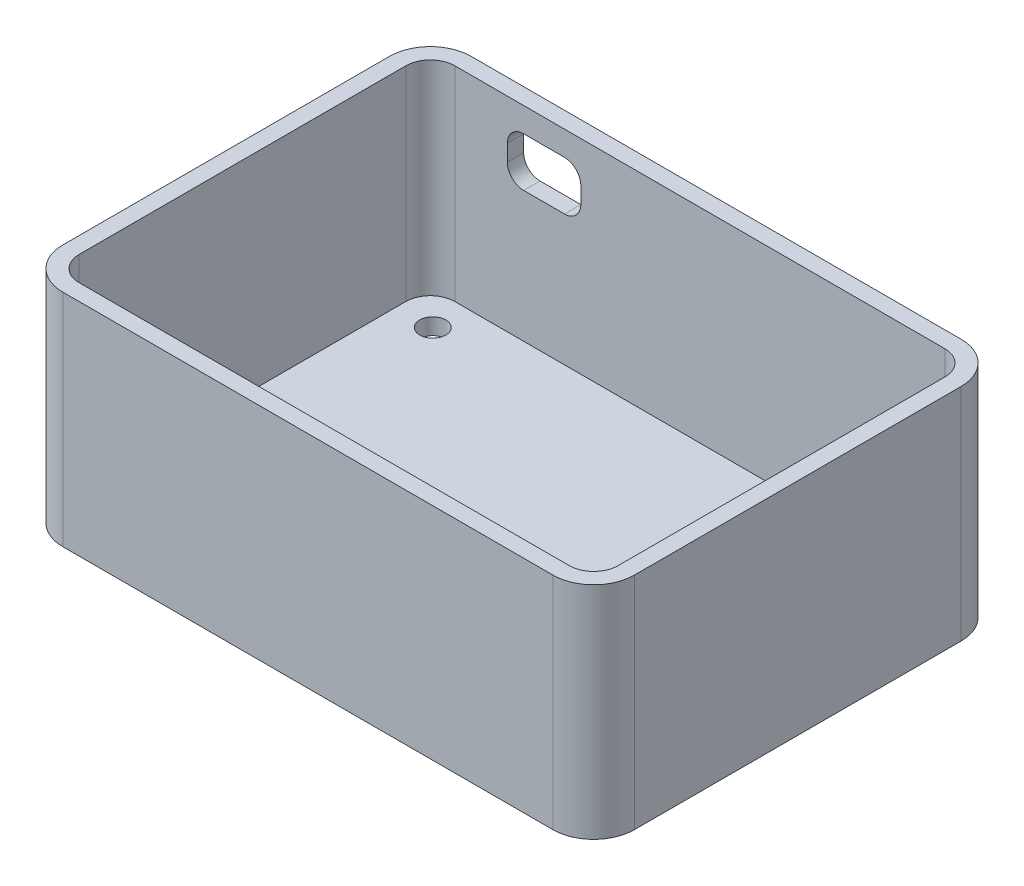
SolidWorks part; units mm, degrees
ref_plane "Front Plane" through (0, 0, 0) normal (0, 0, 1) x (1, 0, 0)
ref_plane "Top Plane" through (0, 0, 0) normal (0, 1, 0) x (1, 0, 0)
ref_plane "Right Plane" through (0, 0, 0) normal (1, 0, 0) x (0, 0, -1)
sketch "Sketch1" plane through (0, 0, 0) normal (0, 1, 0) x (1, 0, 0)
  line L0 (35, 0) -> (35, -50) construction
  line L1 (5, 0) -> (65, 0)
  line L2 (0, -5) -> (0, -45)
  line L3 (5, -50) -> (65, -50)
  line L4 (70, -5) -> (70, -45)
  line L5 (0, -25) -> (70, -25) construction
  circle A0 centre (6.4, -6.1) radius 1.6
  circle A1 centre (63.6, -6.1) radius 1.6
  circle A2 centre (6.4, -43.9) radius 1.6
  circle A3 centre (63.6, -43.9) radius 1.6
  arc A4 (65, -50) -> (70, -45) centre (65, -45) ccw
  arc A5 (0, -45) -> (5, -50) centre (5, -45) ccw
  arc A6 (65, 0) -> (70, -5) centre (65, -5) cw
  arc A7 (5, 0) -> (0, -5) centre (5, -5) ccw
  point P17 (0, 0)
  point P22 (0, -50)
  point P25 (70, 0)
  point P28 (0, 0)
  dimension "D3" = 3.2
  dimension "D4" = 3.2
  dimension "D7" = 3.2
  dimension "D8" = 3.2
  dimension "D11" = 5
  dimension "D1" = 70
  dimension "D2" = 50
  dimension "D5" = 57.2
  dimension "D6" = 28.6
  dimension "D9" = 37.8
  dimension "D10" = 18.9
extrude "Boss-Extrude2" add sketch "Sketch1" along normal blind 2
sketch "Sketch2" plane through (0, 2, 0) normal (0, 1, 0) x (1, 0, 0)
  line L0 (70, -45) -> (70, -5) construction
  line L1 (5, 0) -> (65, 0)
  line L2 (0, -5) -> (0, -45)
  line L3 (5, -50) -> (65, -50)
  line L4 (70, -5) -> (70, -45)
  line L5 (2, -5) -> (2, -45)
  line L6 (5, -48) -> (65, -48)
  line L7 (68, -5) -> (68, -45)
  line L8 (5, -2) -> (65, -2)
  arc A0 (0, -45) -> (5, -50) centre (5, -45) ccw
  arc A1 (65, -50) -> (70, -45) centre (65, -45) ccw
  arc A2 (65, 0) -> (70, -5) centre (65, -5) cw
  arc A3 (5, 0) -> (0, -5) centre (5, -5) ccw
  arc A4 (2, -45) -> (5, -48) centre (5, -45) ccw
  arc A5 (65, -48) -> (68, -45) centre (65, -45) ccw
  arc A6 (65, -2) -> (68, -5) centre (65, -5) cw
  arc A7 (5, -2) -> (2, -5) centre (5, -5) ccw
  point P9 (0, -50)
  point P12 (70, -50)
  point P17 (0, 0)
  dimension "D2" = 5
  dimension "D1" = 50
  dimension "D3" = 2
extrude "Boss-Extrude3" add sketch "Sketch2" along normal blind 25
sketch "Sketch3" plane through (0, 0, 0) normal (0, 0, -1) x (-1, 0, 0)
  line L0 (-65, 27) -> (-5, 27) construction
  line L1 (-13.4287, 24) -> (-18.4287, 24)
  line L2 (-11.4287, 22) -> (-11.4287, 20)
  line L3 (-13.4287, 18) -> (-18.4287, 18)
  line L4 (-20.4287, 22) -> (-20.4287, 20)
  arc A0 (-18.4287, 18) -> (-20.4287, 20) centre (-18.4287, 20) cw
  arc A1 (-11.4287, 20) -> (-13.4287, 18) centre (-13.4287, 20) cw
  arc A2 (-13.4287, 24) -> (-11.4287, 22) centre (-13.4287, 22) cw
  arc A3 (-18.4287, 24) -> (-20.4287, 22) centre (-18.4287, 22) ccw
  point P8 (-11.4287, 18)
  point P11 (-11.4287, 24)
  point P14 (-20.4287, 24)
  dimension "D3" = 2
  dimension "D1" = 6
  dimension "D2" = 9
  dimension "D4" = 3
extrude "Cut-Extrude1" cut sketch "Sketch3" against normal up to next
